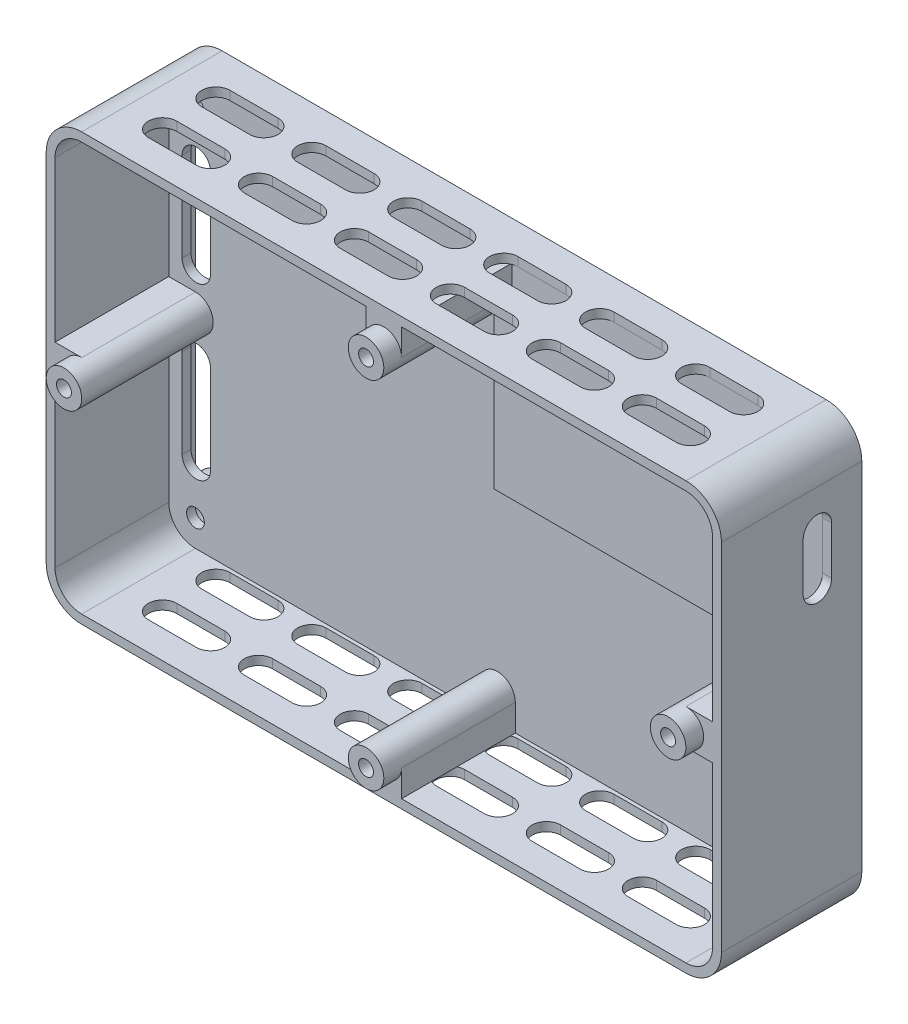
SolidWorks part; units mm, degrees
ref_plane "Front Plane" through (0, 0, 0) normal (0, 0, 1) x (1, 0, 0)
ref_plane "Top Plane" through (0, 0, 0) normal (0, 1, 0) x (1, 0, 0)
ref_plane "Right Plane" through (0, 0, 0) normal (1, 0, 0) x (0, 0, -1)
sketch "Sketch1" plane through (0, 0, 0) normal (0, 0, 1) x (1, 0, 0)
  line L0 (92.3241, -194.8914) -> (92.3241, -94.8914) construction
  line L1 (-85.1759, -202.3914) -> (84.8241, -202.3914) construction
  line L2 (84.8241, -87.3914) -> (-85.1759, -87.3914) construction
  line L3 (-92.6759, -94.8914) -> (-92.6759, -194.8914) construction
  line L4 (-85.1759, -204.8914) -> (84.8241, -204.8914)
  line L5 (94.8241, -194.8914) -> (94.8241, -94.8914)
  line L6 (84.8241, -84.8914) -> (-85.1759, -84.8914)
  line L7 (-95.1759, -94.8914) -> (-95.1759, -194.8914)
  line L8 (-85.1759, -204.8914) -> (84.8241, -204.8914)
  line L9 (94.8241, -194.8914) -> (94.8241, -94.8914)
  line L10 (84.8241, -84.8914) -> (-85.1759, -84.8914)
  line L11 (-95.1759, -94.8914) -> (-95.1759, -194.8914)
  line L12 (92.3241, -194.8914) -> (92.3241, -94.8914)
  line L13 (-85.1759, -202.3914) -> (84.8241, -202.3914)
  line L14 (84.8241, -87.3914) -> (-85.1759, -87.3914)
  line L15 (-92.6759, -94.8914) -> (-92.6759, -194.8914)
  line L16 (-85.1759, -87.3914) -> (-85.1759, -87.2984)
  circle A0 centre (-85.1759, -94.8914) radius 5.5
  circle A1 centre (84.8241, -94.8914) radius 5.9759
  circle A2 centre (84.8241, -194.8914) radius 5.9759
  circle A3 centre (-85.1759, -194.8914) radius 5.9759
  arc A4 (84.8241, -204.8914) -> (94.8241, -194.8914) centre (84.8241, -194.8914) ccw
  arc A5 (94.8241, -94.8914) -> (84.8241, -84.8914) centre (84.8241, -94.8914) ccw
  arc A6 (-85.1759, -84.8914) -> (-95.1759, -94.8914) centre (-85.1759, -94.8914) ccw
  arc A7 (-95.1759, -194.8914) -> (-85.1759, -204.8914) centre (-85.1759, -194.8914) ccw
  arc A8 (84.8241, -204.8914) -> (94.8241, -194.8914) centre (84.8241, -194.8914) ccw
  arc A9 (94.8241, -94.8914) -> (84.8241, -84.8914) centre (84.8241, -94.8914) ccw
  arc A10 (-85.1759, -84.8914) -> (-95.1759, -94.8914) centre (-85.1759, -94.8914) ccw
  arc A11 (-95.1759, -194.8914) -> (-85.1759, -204.8914) centre (-85.1759, -194.8914) ccw
  circle A13 centre (-85.1759, -194.8914) radius 7.5
  circle A14 centre (84.8241, -94.8914) radius 7.5
  circle A15 centre (84.8241, -194.8914) radius 7.5
  arc A16 (-92.6759, -94.8914) -> (-85.1759, -87.3914) centre (-85.1759, -94.8914) ccw
  dimension "D2" = 11
  dimension "D1" = 0
extrude "Boss-Extrude1" add sketch "Sketch1" along normal blind 5
sketch "Sketch2" plane through (0, 0, 5) normal (0, 0, 1) x (1, 0, 0)
  line L4 (-95.1759, -94.8914) -> (-95.1759, -194.8914)
  line L5 (-85.1759, -204.8914) -> (84.8241, -204.8914)
  line L6 (94.8241, -194.8914) -> (94.8241, -94.8914)
  line L7 (84.8241, -84.8914) -> (-85.1759, -84.8914)
  line L8 (-95.1759, -94.8914) -> (-95.1759, -194.8914)
  line L9 (-85.1759, -204.8914) -> (84.8241, -204.8914)
  line L10 (94.8241, -194.8914) -> (94.8241, -94.8914)
  line L11 (84.8241, -84.8914) -> (-85.1759, -84.8914)
  arc A4 (-95.1759, -194.8914) -> (-85.1759, -204.8914) centre (-85.1759, -194.8914) ccw
  arc A5 (84.8241, -204.8914) -> (94.8241, -194.8914) centre (84.8241, -194.8914) ccw
  arc A6 (94.8241, -94.8914) -> (84.8241, -84.8914) centre (84.8241, -94.8914) ccw
  arc A7 (-85.1759, -84.8914) -> (-95.1759, -94.8914) centre (-85.1759, -94.8914) ccw
  arc A8 (-95.1759, -194.8914) -> (-85.1759, -204.8914) centre (-85.1759, -194.8914) ccw
  arc A9 (84.8241, -204.8914) -> (94.8241, -194.8914) centre (84.8241, -194.8914) ccw
  arc A10 (94.8241, -94.8914) -> (84.8241, -84.8914) centre (84.8241, -94.8914) ccw
  arc A11 (-85.1759, -84.8914) -> (-95.1759, -94.8914) centre (-85.1759, -94.8914) ccw
  dimension "D1" = 0
extrude "Boss-Extrude2" add sketch "Sketch2" along normal blind 2.5
sketch "Sketch3" plane through (0, 0, 7.5) normal (0, 0, 1) x (1, 0, 0)
  line L0 (-85.1759, -94.8914) -> (84.8241, -94.8914) construction
  line L1 (84.8241, -94.8914) -> (84.8241, -194.8914) construction
  line L2 (84.8241, -194.8914) -> (-85.1759, -194.8914) construction
  line L3 (-85.1759, -194.8914) -> (-85.1759, -94.8914) construction
  line L8 (-85.1759, -204.8914) -> (84.8241, -204.8914) construction
  line L9 (94.8241, -194.8914) -> (94.8241, -94.8914) construction
  line L10 (84.8241, -84.8914) -> (-85.1759, -84.8914) construction
  line L11 (-95.1759, -94.8914) -> (-95.1759, -194.8914) construction
  line L12 (-92.6759, -94.8914) -> (-92.6759, -194.8914)
  line L13 (-85.1759, -202.3914) -> (84.8241, -202.3914)
  line L14 (92.3241, -194.8914) -> (92.3241, -94.8914)
  line L15 (84.8241, -87.3914) -> (-85.1759, -87.3914)
  line L16 (-92.6759, -94.8914) -> (-92.6759, -194.8914)
  line L17 (-85.1759, -202.3914) -> (84.8241, -202.3914)
  line L18 (92.3241, -194.8914) -> (92.3241, -94.8914)
  line L19 (84.8241, -87.3914) -> (-85.1759, -87.3914)
  line L20 (-85.1759, -204.8914) -> (84.8241, -204.8914)
  line L21 (94.8241, -194.8914) -> (94.8241, -94.8914)
  line L22 (84.8241, -84.8914) -> (-85.1759, -84.8914)
  line L23 (-95.1759, -94.8914) -> (-95.1759, -194.8914)
  line L24 (-85.1759, -139.8914) -> (-92.6759, -139.8914)
  line L25 (-85.1759, -149.8914) -> (-92.6759, -149.8914)
  line L26 (-5.1759, -94.8914) -> (-5.1759, -87.3914)
  line L27 (4.8241, -94.8914) -> (4.8241, -87.3914)
  line L28 (-5.1759, -194.8914) -> (-5.1759, -202.3914)
  line L29 (4.8241, -194.8914) -> (4.8241, -202.3914)
  line L30 (84.8241, -139.8914) -> (92.3241, -139.8914)
  line L33 (84.8241, -149.8914) -> (92.3241, -149.8914)
  circle A0 centre (-0.1759, -94.8914) radius 5
  circle A1 centre (-85.1759, -144.8914) radius 5
  circle A2 centre (-0.1759, -194.8914) radius 5
  circle A3 centre (84.8241, -144.8914) radius 5
  arc A8 (-95.1759, -194.8914) -> (-85.1759, -204.8914) centre (-85.1759, -194.8914) ccw construction
  arc A9 (84.8241, -204.8914) -> (94.8241, -194.8914) centre (84.8241, -194.8914) ccw construction
  arc A10 (94.8241, -94.8914) -> (84.8241, -84.8914) centre (84.8241, -94.8914) ccw construction
  arc A11 (-85.1759, -84.8914) -> (-95.1759, -94.8914) centre (-85.1759, -94.8914) ccw construction
  arc A12 (-85.1759, -87.3914) -> (-92.6759, -94.8914) centre (-85.1759, -94.8914) ccw
  arc A13 (-92.6759, -194.8914) -> (-85.1759, -202.3914) centre (-85.1759, -194.8914) ccw
  arc A14 (84.8241, -202.3914) -> (92.3241, -194.8914) centre (84.8241, -194.8914) ccw
  arc A15 (92.3241, -94.8914) -> (84.8241, -87.3914) centre (84.8241, -94.8914) ccw
  arc A16 (-85.1759, -87.3914) -> (-92.6759, -94.8914) centre (-85.1759, -94.8914) ccw
  arc A17 (-92.6759, -194.8914) -> (-85.1759, -202.3914) centre (-85.1759, -194.8914) ccw
  arc A18 (84.8241, -202.3914) -> (92.3241, -194.8914) centre (84.8241, -194.8914) ccw
  arc A19 (92.3241, -94.8914) -> (84.8241, -87.3914) centre (84.8241, -94.8914) ccw
  arc A20 (-95.1759, -194.8914) -> (-85.1759, -204.8914) centre (-85.1759, -194.8914) ccw
  arc A21 (84.8241, -204.8914) -> (94.8241, -194.8914) centre (84.8241, -194.8914) ccw
  arc A22 (94.8241, -94.8914) -> (84.8241, -84.8914) centre (84.8241, -94.8914) ccw
  arc A23 (-85.1759, -84.8914) -> (-95.1759, -94.8914) centre (-85.1759, -94.8914) ccw
  arc M9 (-85.1759, -84.8914) -> (-95.1759, -94.8914) centre (-85.1759, -94.8914) ccw
  line M10 (-95.1759, -94.8914) -> (-95.1759, -194.8914)
  arc M11 (-95.1759, -194.8914) -> (-85.1759, -204.8914) centre (-85.1759, -194.8914) ccw
  line M12 (-85.1759, -204.8914) -> (84.8241, -204.8914)
  arc M13 (84.8241, -204.8914) -> (94.8241, -194.8914) centre (84.8241, -194.8914) ccw
  line M14 (94.8241, -194.8914) -> (94.8241, -94.8914)
  arc M15 (94.8241, -94.8914) -> (84.8241, -84.8914) centre (84.8241, -94.8914) ccw
  line M16 (84.8241, -84.8914) -> (-85.1759, -84.8914)
  dimension "D1" = 10
  dimension "D2" = 2.5
extrude "Boss-Extrude3" add sketch "Sketch3" along normal blind 32 contours A19 L18 A18 L17 A17 L16 A16 L19 M16 M9 M10 M11 M12 M13 M14 M15 | A0 L27 L19 L26 | A0 | A3 | A3 L33 L18 L30 | A2 | A2 L28 L17 L29 | A1 L24 L16 L25 | A1
sketch "Sketch5" plane through (0, 0, 39.5) normal (0, 0, 1) x (1, 0, 0)
  circle A0 centre (-85.1759, -144.8914) radius 5
  circle A1 centre (-0.1759, -94.8914) radius 5
  circle A2 centre (84.8241, -144.8914) radius 5
  circle A3 centre (-0.1759, -194.8914) radius 5
extrude "Boss-Extrude4" add sketch "Sketch5" along normal blind 5
sketch "Sketch6" plane through (0, 0, 7.5) normal (0, 0, 1) x (1, 0, 0)
  line L2 (-80.9375, -181.3615) -> (-80.9375, -156.298)
  line L3 (-88.9375, -156.298) -> (-88.9375, -181.3615)
  line L4 (-80.9375, -181.3615) -> (-80.9375, -156.298)
  line L5 (-88.9375, -156.298) -> (-88.9375, -181.3615)
  line L6 (-80.9375, -133.4848) -> (-80.9375, -108.4213)
  line L7 (-88.9375, -108.4213) -> (-88.9375, -133.4848)
  line L8 (-80.9375, -133.4848) -> (-80.9375, -108.4213)
  line L9 (-88.9375, -108.4213) -> (-88.9375, -133.4848)
  arc A2 (-80.9375, -156.298) -> (-88.9375, -156.298) centre (-84.9375, -156.298) ccw
  arc A3 (-88.9375, -181.3615) -> (-80.9375, -181.3615) centre (-84.9375, -181.3615) ccw
  arc A4 (-80.9375, -156.298) -> (-88.9375, -156.298) centre (-84.9375, -156.298) ccw
  arc A5 (-88.9375, -181.3615) -> (-80.9375, -181.3615) centre (-84.9375, -181.3615) ccw
  arc A6 (-88.9375, -133.4848) -> (-80.9375, -133.4848) centre (-84.9375, -133.4848) ccw
  arc A7 (-80.9375, -108.4213) -> (-88.9375, -108.4213) centre (-84.9375, -108.4213) ccw
  arc A8 (-88.9375, -133.4848) -> (-80.9375, -133.4848) centre (-84.9375, -133.4848) ccw
  arc A9 (-80.9375, -108.4213) -> (-88.9375, -108.4213) centre (-84.9375, -108.4213) ccw
  dimension "D1" = 0
  dimension "D2" = 0
extrude "Cut-Extrude1" cut sketch "Sketch6" against normal blind 5
hole_wizard "Tap Drill for M5 Tap2" positions "Sketch12" profile "Sketch11" hole size "M5" standard "ISO"
sketch "Sketch12" plane through (0, 0, 44.5) normal (0, 0, 1) x (1, 0, 0)
  point P0 (-0.1759, -94.8914)
  point P3 (-85.1759, -144.8914)
  point P6 (84.8241, -144.8914)
  point P9 (-0.1759, -194.8914)
sketch "Sketch11" plane through (-0.1759, -94.8914, 44.5) normal (1, 0, 0) x (0, -1, 0)
  line L0 (0, 0) -> (0, 21.2618)
  line L1 (0, 21.2618) -> (2.1, 20)
  line L2 (2.1, 20) -> (2.1, 0)
  line L5 (2.1, 0) -> (0, 0)
  line L10 (0, 21.2618) -> (-2.1, 20) construction
  line L11 (0, -6.35) -> (0, 107.95) construction
  dimension "Hole Dia." = 4.2
  dimension "Hole Depth" = 20
  dimension "Drill Angle" = 118
hole_wizard "Ø5.0 (5) Diameter Hole1" positions "Sketch13" profile "Sketch14" hole size "Ø5.0" standard "ISO"
sketch "Sketch13" plane through (0, 0, 7.5) normal (0, 0, 1) x (1, 0, 0)
  point P0 (-85.1759, -94.8914)
  point P3 (-85.1759, -94.8914)
  point P6 (-85.1759, -194.8914)
  point P9 (84.8241, -194.8914)
  point P12 (84.8241, -94.8914)
sketch "Sketch14" plane through (-85.1759, -94.8914, 7.5) normal (1, 0, 0) x (0, -1, 0)
  line L0 (0, 0) -> (0, 4.0022)
  line L1 (0, 4.0022) -> (2.5, 2.5)
  line L2 (2.5, 2.5) -> (2.5, 0)
  line L5 (2.5, 0) -> (0, 0)
  line L10 (0, 4.0022) -> (-2.5, 2.5) construction
  line L11 (0, -6.35) -> (0, 107.95) construction
  dimension "Hole Dia." = 5
  dimension "Hole Depth" = 2.5
  dimension "Drill Angle" = 118
sketch "Sketch20" plane through (0, -204.8914, 0) normal (0, -1, 0) x (1, 0, 0)
  line L0 (-47.4259, 27.5) -> (-33.9259, 27.5) construction
  line L3 (-74.4259, 32.9107) -> (-74.4259, 6.1392) construction
  line L4 (-85.1759, 39.5) -> (-85.1759, 0) construction
  line L5 (-85.1759, 39.5) -> (84.8241, 39.5) construction
  line L7 (-74.4259, 27.5) -> (-60.9259, 27.5) construction
  line L8 (-74.4259, 31.5) -> (-60.9259, 31.5)
  line L9 (-74.4259, 23.5) -> (-60.9259, 23.5)
  line L10 (-47.4259, 31.5) -> (-33.9259, 31.5)
  line L13 (-47.4259, 23.5) -> (-33.9259, 23.5)
  line L16 (-20.4259, 27.5) -> (-6.9259, 27.5) construction
  line L19 (-20.4259, 31.5) -> (-6.9259, 31.5)
  line L22 (-20.4259, 23.5) -> (-6.9259, 23.5)
  line L25 (6.5741, 27.5) -> (20.0741, 27.5) construction
  line L28 (6.5741, 31.5) -> (20.0741, 31.5)
  line L31 (6.5741, 23.5) -> (20.0741, 23.5)
  line L34 (33.5741, 27.5) -> (47.0741, 27.5) construction
  line L37 (33.5741, 31.5) -> (47.0741, 31.5)
  line L40 (33.5741, 23.5) -> (47.0741, 23.5)
  line L43 (60.5741, 27.5) -> (74.0741, 27.5) construction
  line L44 (60.5741, 31.5) -> (74.0741, 31.5)
  line L45 (60.5741, 23.5) -> (74.0741, 23.5)
  line L46 (-47.4259, 12.5) -> (-33.9259, 12.5) construction
  line L47 (-47.4259, 16.5) -> (-33.9259, 16.5)
  line L48 (-47.4259, 8.5) -> (-33.9259, 8.5)
  line L49 (-20.4259, 12.5) -> (-6.9259, 12.5) construction
  line L50 (-20.4259, 16.5) -> (-6.9259, 16.5)
  line L51 (-20.4259, 8.5) -> (-6.9259, 8.5)
  line L52 (6.5741, 12.5) -> (20.0741, 12.5) construction
  line L53 (6.5741, 16.5) -> (20.0741, 16.5)
  line L54 (6.5741, 8.5) -> (20.0741, 8.5)
  line L55 (33.5741, 12.5) -> (47.0741, 12.5) construction
  line L56 (33.5741, 16.5) -> (47.0741, 16.5)
  line L57 (33.5741, 8.5) -> (47.0741, 8.5)
  line L58 (60.5741, 12.5) -> (74.0741, 12.5) construction
  line L59 (60.5741, 16.5) -> (74.0741, 16.5)
  line L60 (60.5741, 8.5) -> (74.0741, 8.5)
  line L61 (-74.4259, 12.5) -> (-60.9259, 12.5) construction
  line L62 (-74.4259, 16.5) -> (-60.9259, 16.5)
  line L63 (-74.4259, 8.5) -> (-60.9259, 8.5)
  line L64 (-74.4259, 27.5) -> (-47.4259, 27.5) construction
  line L65 (-74.4259, 27.5) -> (-74.4259, 12.5) construction
  arc A0 (-74.4259, 31.5) -> (-74.4259, 23.5) centre (-74.4259, 27.5) ccw
  arc A1 (-60.9259, 23.5) -> (-60.9259, 31.5) centre (-60.9259, 27.5) ccw
  arc A24 (-47.4259, 31.5) -> (-47.4259, 23.5) centre (-47.4259, 27.5) ccw
  arc A25 (-33.9259, 23.5) -> (-33.9259, 31.5) centre (-33.9259, 27.5) ccw
  arc A26 (-20.4259, 31.5) -> (-20.4259, 23.5) centre (-20.4259, 27.5) ccw
  arc A27 (-6.9259, 23.5) -> (-6.9259, 31.5) centre (-6.9259, 27.5) ccw
  arc A28 (6.5741, 31.5) -> (6.5741, 23.5) centre (6.5741, 27.5) ccw
  arc A29 (20.0741, 23.5) -> (20.0741, 31.5) centre (20.0741, 27.5) ccw
  arc A30 (33.5741, 31.5) -> (33.5741, 23.5) centre (33.5741, 27.5) ccw
  arc A31 (47.0741, 23.5) -> (47.0741, 31.5) centre (47.0741, 27.5) ccw
  arc A32 (60.5741, 31.5) -> (60.5741, 23.5) centre (60.5741, 27.5) ccw
  arc A33 (74.0741, 23.5) -> (74.0741, 31.5) centre (74.0741, 27.5) ccw
  arc A34 (-47.4259, 16.5) -> (-47.4259, 8.5) centre (-47.4259, 12.5) ccw
  arc A35 (-33.9259, 8.5) -> (-33.9259, 16.5) centre (-33.9259, 12.5) ccw
  arc A36 (-20.4259, 16.5) -> (-20.4259, 8.5) centre (-20.4259, 12.5) ccw
  arc A37 (-6.9259, 8.5) -> (-6.9259, 16.5) centre (-6.9259, 12.5) ccw
  arc A38 (6.5741, 16.5) -> (6.5741, 8.5) centre (6.5741, 12.5) ccw
  arc A39 (20.0741, 8.5) -> (20.0741, 16.5) centre (20.0741, 12.5) ccw
  arc A40 (33.5741, 16.5) -> (33.5741, 8.5) centre (33.5741, 12.5) ccw
  arc A41 (47.0741, 8.5) -> (47.0741, 16.5) centre (47.0741, 12.5) ccw
  arc A42 (60.5741, 16.5) -> (60.5741, 8.5) centre (60.5741, 12.5) ccw
  arc A43 (74.0741, 8.5) -> (74.0741, 16.5) centre (74.0741, 12.5) ccw
  arc A44 (-74.4259, 16.5) -> (-74.4259, 8.5) centre (-74.4259, 12.5) ccw
  arc A45 (-60.9259, 8.5) -> (-60.9259, 16.5) centre (-60.9259, 12.5) ccw
  point P4 (-40.6759, 27.5)
  point P18 (-67.6759, 27.5)
  point P23 (-78.4259, 27.5)
  point P27 (-13.6759, 27.5)
  point P34 (13.3241, 27.5)
  point P41 (40.3241, 27.5)
  point P48 (67.3241, 27.5)
  point P55 (-40.6759, 12.5)
  point P62 (-13.6759, 12.5)
  point P69 (13.3241, 12.5)
  point P76 (40.3241, 12.5)
  point P83 (67.3241, 12.5)
  point P90 (-67.6759, 12.5)
  dimension "D4" = 13.5
  dimension "D5" = 8
  dimension "D1" = 10.75
  dimension "D2" = 39.5
  dimension "D3" = 12
  dimension "D8" = 27
  dimension "D9" = 15
  dimension "D6" = 6
  dimension "D7" = 2
extrude "Cut-Extrude4" cut sketch "Sketch20" against normal blind 2.5
sketch "Sketch21" plane through (0, -84.8914, 0) normal (0, 1, 0) x (1, 0, 0)
  line L0 (74.0741, -31.5) -> (60.5741, -31.5) construction
  line L1 (60.5741, -23.5) -> (74.0741, -23.5) construction
  line L2 (74.0741, -31.5) -> (60.5741, -31.5)
  line L3 (60.5741, -23.5) -> (74.0741, -23.5)
  line L4 (47.0741, -31.5) -> (33.5741, -31.5)
  line L5 (33.5741, -23.5) -> (47.0741, -23.5)
  line L6 (20.0741, -31.5) -> (6.5741, -31.5)
  line L7 (6.5741, -23.5) -> (20.0741, -23.5)
  line L8 (-6.9259, -31.5) -> (-20.4259, -31.5)
  line L9 (-20.4259, -23.5) -> (-6.9259, -23.5)
  line L10 (-33.9259, -31.5) -> (-47.4259, -31.5)
  line L11 (-47.4259, -23.5) -> (-33.9259, -23.5)
  line L12 (-60.9259, -31.5) -> (-74.4259, -31.5)
  line L13 (-74.4259, -23.5) -> (-60.9259, -23.5)
  line L14 (47.0741, -16.5) -> (33.5741, -16.5)
  line L15 (33.5741, -8.5) -> (47.0741, -8.5)
  line L16 (20.0741, -16.5) -> (6.5741, -16.5)
  line L17 (6.5741, -8.5) -> (20.0741, -8.5)
  line L18 (-6.9259, -16.5) -> (-20.4259, -16.5)
  line L19 (-20.4259, -8.5) -> (-6.9259, -8.5)
  line L20 (-33.9259, -16.5) -> (-47.4259, -16.5)
  line L21 (-47.4259, -8.5) -> (-33.9259, -8.5)
  line L22 (-60.9259, -16.5) -> (-74.4259, -16.5)
  line L23 (-74.4259, -8.5) -> (-60.9259, -8.5)
  line L24 (74.0741, -16.5) -> (60.5741, -16.5)
  line L25 (60.5741, -8.5) -> (74.0741, -8.5)
  line L26 (74.0741, -31.5) -> (47.0741, -31.5) construction
  line L27 (74.0741, -31.5) -> (74.0741, -16.5) construction
  arc A0 (60.5741, -23.5) -> (60.5741, -31.5) centre (60.5741, -27.5) ccw construction
  arc A1 (74.0741, -31.5) -> (74.0741, -23.5) centre (74.0741, -27.5) ccw construction
  arc A2 (60.5741, -23.5) -> (60.5741, -31.5) centre (60.5741, -27.5) ccw
  arc A3 (74.0741, -31.5) -> (74.0741, -23.5) centre (74.0741, -27.5) ccw
  arc A4 (33.5741, -23.5) -> (33.5741, -31.5) centre (33.5741, -27.5) ccw
  arc A5 (47.0741, -31.5) -> (47.0741, -23.5) centre (47.0741, -27.5) ccw
  arc A6 (6.5741, -23.5) -> (6.5741, -31.5) centre (6.5741, -27.5) ccw
  arc A7 (20.0741, -31.5) -> (20.0741, -23.5) centre (20.0741, -27.5) ccw
  arc A8 (-20.4259, -23.5) -> (-20.4259, -31.5) centre (-20.4259, -27.5) ccw
  arc A9 (-6.9259, -31.5) -> (-6.9259, -23.5) centre (-6.9259, -27.5) ccw
  arc A10 (-47.4259, -23.5) -> (-47.4259, -31.5) centre (-47.4259, -27.5) ccw
  arc A11 (-33.9259, -31.5) -> (-33.9259, -23.5) centre (-33.9259, -27.5) ccw
  arc A12 (-74.4259, -23.5) -> (-74.4259, -31.5) centre (-74.4259, -27.5) ccw
  arc A13 (-60.9259, -31.5) -> (-60.9259, -23.5) centre (-60.9259, -27.5) ccw
  arc A14 (33.5741, -8.5) -> (33.5741, -16.5) centre (33.5741, -12.5) ccw
  arc A15 (47.0741, -16.5) -> (47.0741, -8.5) centre (47.0741, -12.5) ccw
  arc A16 (6.5741, -8.5) -> (6.5741, -16.5) centre (6.5741, -12.5) ccw
  arc A17 (20.0741, -16.5) -> (20.0741, -8.5) centre (20.0741, -12.5) ccw
  arc A18 (-20.4259, -8.5) -> (-20.4259, -16.5) centre (-20.4259, -12.5) ccw
  arc A19 (-6.9259, -16.5) -> (-6.9259, -8.5) centre (-6.9259, -12.5) ccw
  arc A20 (-47.4259, -8.5) -> (-47.4259, -16.5) centre (-47.4259, -12.5) ccw
  arc A21 (-33.9259, -16.5) -> (-33.9259, -8.5) centre (-33.9259, -12.5) ccw
  arc A22 (-74.4259, -8.5) -> (-74.4259, -16.5) centre (-74.4259, -12.5) ccw
  arc A23 (-60.9259, -16.5) -> (-60.9259, -8.5) centre (-60.9259, -12.5) ccw
  arc A24 (60.5741, -8.5) -> (60.5741, -16.5) centre (60.5741, -12.5) ccw
  arc A25 (74.0741, -16.5) -> (74.0741, -8.5) centre (74.0741, -12.5) ccw
  dimension "D3" = 90
  dimension "D4" = 27
  dimension "D1" = 6
  dimension "D2" = 2
extrude "Cut-Extrude5" cut sketch "Sketch21" against normal blind 2.5
sketch "Sketch24" plane through (94.8241, -110.0673, 0) normal (-1, 0, 0) x (0, -1, 0)
  line L2 (-4.4259, 8.5) -> (9.0741, 8.5)
  line L3 (9.0741, 16.5) -> (-4.4259, 16.5)
  line L4 (-15.1759, 39.5) -> (-15.1759, 0) construction
  arc A2 (9.0741, 8.5) -> (9.0741, 16.5) centre (9.0741, 12.5) ccw
  arc A3 (-4.4259, 16.5) -> (-4.4259, 8.5) centre (-4.4259, 12.5) ccw
  dimension "D1" = 10.75
extrude "Cut-Extrude7" cut sketch "Sketch24" along normal blind 2.5
sketch "Sketch25" plane through (0, 0, 7.5) normal (0, 0, 1) x (1, 0, 0)
  line L1 (-0.1759, -87.3914) -> (84.8241, -87.3914)
  line L2 (-0.1759, -87.3914) -> (-0.1759, -144.8914)
  line L3 (-0.1759, -144.8914) -> (92.3241, -144.8914)
  line L4 (92.3241, -94.8914) -> (92.3241, -144.8914)
  circle A0 centre (84.8241, -94.8914) radius 7.5
  line M19 (84.8241, -87.3914) -> (4.8241, -87.3914)
  line M20 (4.8241, -87.3914) -> (4.8241, -94.8914)
  arc M21 (4.8241, -94.8914) -> (-5.1759, -94.8914) centre (-0.1759, -94.8914) cw
  arc M39 (84.8241, -149.8914) -> (84.8241, -139.8914) centre (84.8241, -144.8914) cw
  line M40 (84.8241, -139.8914) -> (92.3241, -139.8914)
  line M41 (92.3241, -139.8914) -> (92.3241, -94.8914)
extrude "Boss-Extrude5" add sketch "Sketch25" along normal up to surface (1 mm away) separate body contours A0 L2 L3 M19 M20 M21 M39 M40 M41 up to face at (93.5741, -112.3914, 8.5)
